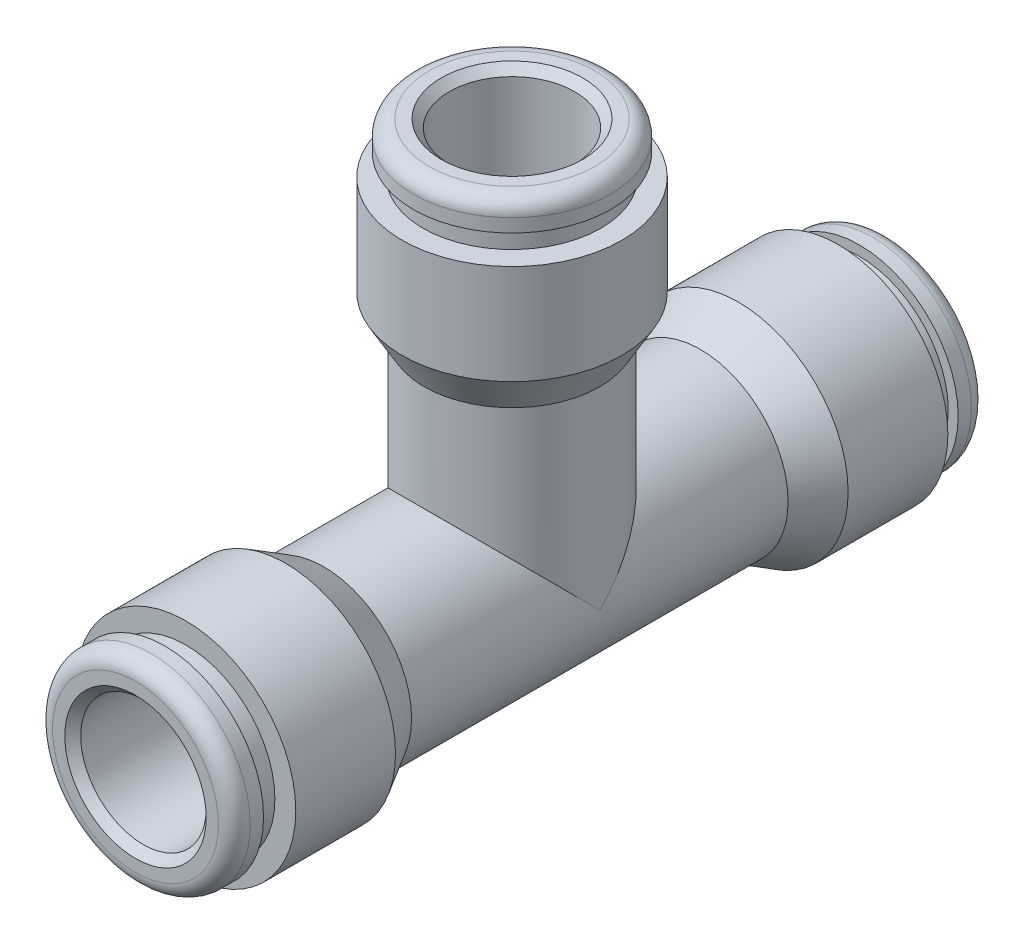
SolidWorks part; units mm, degrees
ref_plane "Front Plane" through (0, 0, 0) normal (0, 0, 1) x (1, 0, 0)
ref_plane "Top Plane" through (0, 0, 0) normal (0, 1, 0) x (1, 0, 0)
ref_plane "Right Plane" through (0, 0, 0) normal (1, 0, 0) x (0, 0, -1)
sketch "Sketch1" plane through (0, 0, 0) normal (1, 0, 0) x (0, 0, -1)
  line L0 (16.603, 4.725) -> (17.238, 4.725)
  line L1 (10.8187, 5.25) -> (15.587, 5.25)
  line L2 (0, 4.2) -> (0, 2.238)
  line L3 (5.75, 3) -> (17.619, 3)
  line L4 (18, 3.963) -> (18, 3.381)
  line L5 (0, 0) -> (0, 18.25) construction
  line L6 (15.587, 5.25) -> (15.587, 4.2525)
  line L7 (15.587, 4.2525) -> (16.603, 4.2525)
  line L8 (16.603, 4.725) -> (16.603, 4.2525)
  line L9 (-5.25, 18.25) -> (5.25, 18.25) construction
  line L10 (0, 0) -> (18, 0) construction
  line L11 (5.75, 3) -> (5.75, 2.238)
  line L12 (17.619, 3) -> (18, 3.381)
  line L13 (0, 0) -> (0, 2.238) construction
  line L14 (0, 4.2) -> (9, 4.2)
  line L15 (9, 4.2) -> (10.8187, 5.25)
  line L16 (5.75, 2.238) -> (0, 2.238)
  line L17 (0, 18) -> (0, 0) construction
  line L22 (0, 0) -> (-18, 0) construction
  arc A0 (17.238, 4.725) -> (18, 3.963) centre (17.238, 3.963) cw
  point P1 (18, 3)
  point P2 (18, 5.25)
  point P17 (18, -5.25)
  point P20 (18, 4.725)
  point P26 (-18, -5.25)
  dimension "D4" = 0.762
  dimension "tube od" = 6
  dimension "D1" = 1.397
  dimension "D2" = 1.016
  dimension "D3" = 8.505
  dimension "D6" = 9.45
  dimension "D9" = 30
  dimension "D10" = 8.4
  dimension "D5" = 9
  dimension "D8" = 10.5
  dimension "D11" = 0.762
revolve "Revolve1" add sketch "Sketch1" angle 360 about L10
ref_axis "Axis1" through (-5.775, 0, 0) along (1, 0, 0)
pattern_circular "CirPattern1" count 3 over 180 about axis through (0, 0, 0) along (1, 0, 0) of bodies 118 123
move or copy body "Body-Move/Copy1" bodies to move or copy 124 copy no translate (0, 0.25, 0)
sketch "Sketch3" plane through (0, 0, 0) normal (0, 1, 0) x (1, 0, 0)
  circle A0 centre (0, 0) radius 4.2 construction
  circle A1 centre (0, 0) radius 4.2
extrude "Boss-Extrude1" add sketch "Sketch3" along normal up to surface (0.25 mm away) up to face at (2.238, 0.25, 0)
sketch "Sketch4" plane through (0, 0, 0) normal (1, 0, 0) x (0, 0, -1)
  line L0 (3, 17.869) -> (3.381, 18.25)
  line L1 (3.381, 18.25) -> (0, 18.25)
  line L2 (0, 18.25) -> (0, 0)
  line L4 (2.238, 0) -> (2.238, 6)
  line L5 (2.238, 6) -> (3, 6)
  line L6 (3, 6) -> (3, 17.869)
  line L7 (2.238, 0) -> (0, 0)
  line L9 (2.238, 6) -> (-2.238, 6) construction
  line L10 (3, 6) -> (-3, 6) construction
revolve "Cut-Revolve2" cut sketch "Sketch4" angle 360 about L5
combine bodies "Combine1" operation type add bodies to combine 145 148 146
sketch "Sketch5" plane through (0, 0, 0) normal (1, 0, 0) x (0, 0, -1)
  line L0 (18, 3.381) -> (17.619, 3)
  line L1 (17.619, 3) -> (5.75, 3)
  line L2 (5.75, 3) -> (5.75, 2.238)
  line L3 (5.75, 2.238) -> (0, 2.238)
  line L4 (0, 2.238) -> (0, 0)
  line L5 (0, 0) -> (18, 0)
  line L6 (18, 0) -> (18, 3.381)
revolve "Cut-Revolve1" cut sketch "Sketch5" angle 360 about L5
pattern_circular "CirPattern2" count 2 over 180 about axis through (-5.775, 0, 0) along (1, 0, 0) of "Cut-Revolve1"
equation "\"D6@Sketch1\" = \"G@Sketch1\"*.9"
equation "\"D3@Sketch1\" = \"D6@Sketch1\"*.9"
equation "\"D10@Sketch1\" = \"G@Sketch1\"*.8"
equation "\"D5@Sketch1\" = \"L/2@Sketch1\"*.5"
equation "\"D8@Sketch1\" = \"G@Sketch1\""
